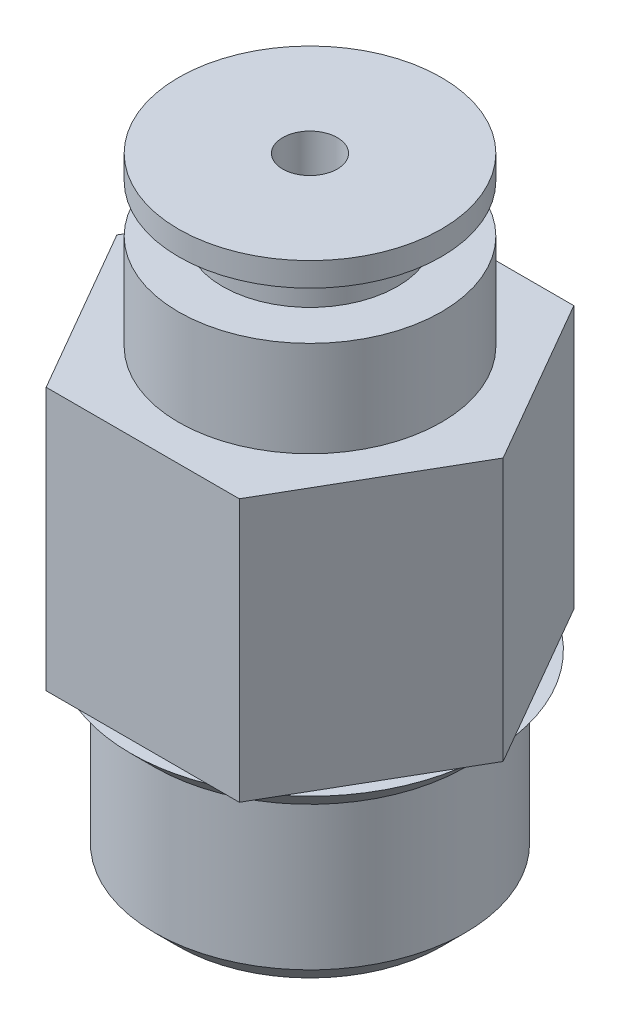
SolidWorks part; units mm, degrees
ref_plane "Front Plane" through (0, 0, 0) normal (0, 0, 1) x (1, 0, 0)
ref_plane "Top Plane" through (0, 0, 0) normal (0, 1, 0) x (1, 0, 0)
ref_plane "Right Plane" through (0, 0, 0) normal (1, 0, 0) x (0, 0, -1)
sketch "Sketch1" plane through (0, 0, 0) normal (0, 0, 1) x (1, 0, 0)
  line L0 (0, 18.9063) -> (0, -22.4336) construction
  line L1 (3.2765, 0) -> (6.5, 0)
  line L2 (6.5, 0) -> (6.5, 7)
  line L3 (6.5, 7) -> (7.5, 8)
  line L4 (7.5, 8) -> (3.2765, 8)
  line L5 (3.2765, 8) -> (3.2765, 0)
  dimension "D1" = 13
  dimension "D2" = 8
  dimension "D3" = 45
  dimension "D4" = 1
revolve "Revolve1" add sketch "Sketch1" angle 360 about L0
sketch "Sketch2" plane through (0, 8, 0) normal (0, 1, 0) x (1, 0, 0)
  line L1 (8.0829, 0) -> (4.0415, 7)
  line L2 (4.0415, 7) -> (-4.0415, 7)
  line L3 (-4.0415, 7) -> (-8.0829, 0)
  line L4 (-8.0829, 0) -> (-4.0415, -7)
  line L5 (-4.0415, -7) -> (4.0415, -7)
  line L6 (4.0415, -7) -> (8.0829, 0)
  circle A0 centre (0, 0) radius 7 construction
  dimension "D1" = 14
extrude "Boss-Extrude1" add sketch "Sketch2" along normal blind 11
sketch "Sketch3" plane through (0, 0, 0) normal (0, 0, 1) x (1, 0, 0)
  line L0 (0, 22.9252) -> (0, -5.3788) construction
  line L1 (5.5, 19) -> (5.5, 23)
  line L2 (4.0415, 19) -> (8.0829, 19) construction
  line L3 (5.5, 23) -> (3.6579, 23)
  line L4 (3.6579, 23) -> (3.6579, 25)
  line L5 (3.6579, 25) -> (5.5, 25)
  line L6 (5.5, 25) -> (5.5, 26)
  line L7 (5.5, 26) -> (1.1423, 26)
  line L8 (1.1423, 26) -> (1.1423, 19)
  line L9 (-4.0415, 19) -> (4.0415, 19) construction
  line L10 (1.1423, 19) -> (5.5, 19)
  dimension "D1" = 4
  dimension "D2" = 2
  dimension "D3" = 1
  dimension "D4" = 11
revolve "Revolve3" add sketch "Sketch3" angle 360 about L0
chamfer "Chamfer1" distance 1 angle 45 1 edges at (0, 0, 6.5)
